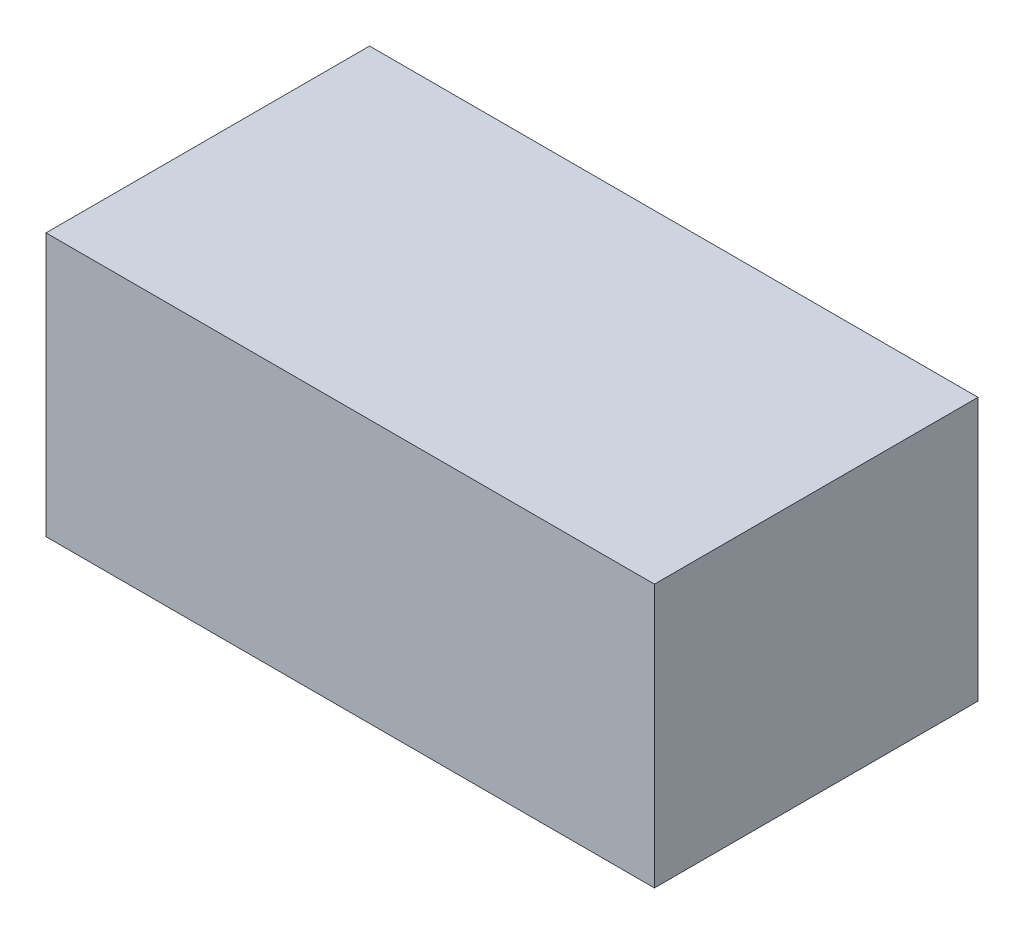
SolidWorks part; units mm, degrees
ref_plane "Front Plane" through (0, 0, 0) normal (0, 0, 1) x (1, 0, 0)
ref_plane "Top Plane" through (0, 0, 0) normal (0, 1, 0) x (1, 0, 0)
ref_plane "Right Plane" through (0, 0, 0) normal (1, 0, 0) x (0, 0, -1)
other "Configuration Table"
sketch "Sketch1" plane through (0, 0, 0) normal (0, 0, 1) x (1, 0, 0)
  line L1 (-71.6422, 39.3582) -> (0, 39.3582)
  line L2 (-71.6422, 39.3582) -> (-71.6422, -30.9846)
  line L3 (-71.6422, -30.9846) -> (0, -30.9846)
  line L4 (0, 39.3582) -> (0, -30.9846)
extrude "Boss-Extrude1" add sketch "Sketch1" along normal blind 38.1
other "SurfaceCut1"
